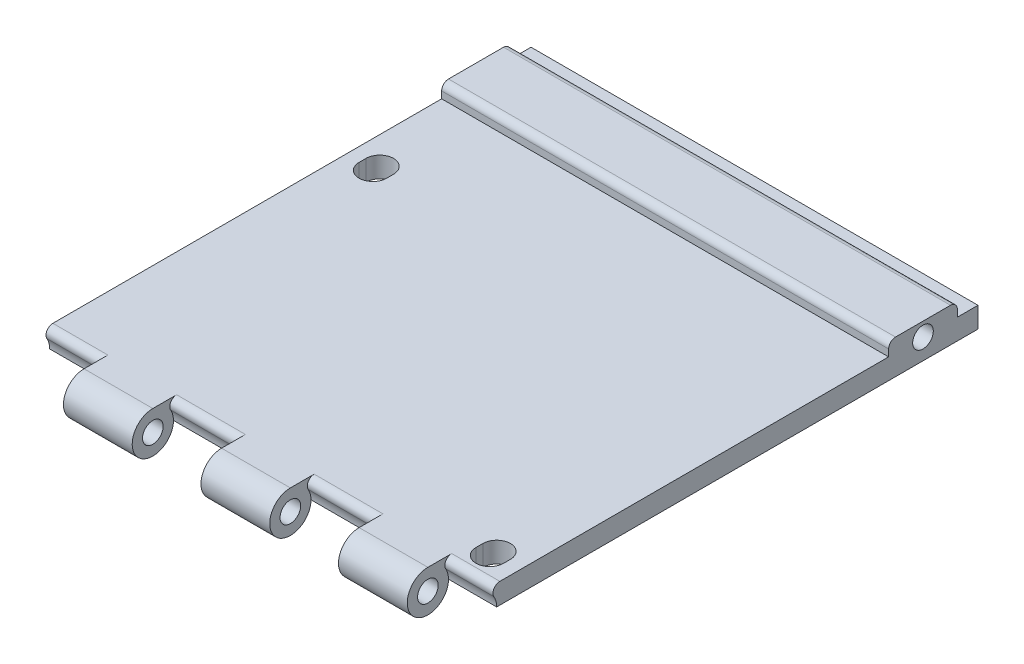
SolidWorks part; units mm, degrees
material "ABS"
ref_plane "Front Plane" through (0, 0, 0) normal (0, 0, 1) x (1, 0, 0)
ref_plane "Top Plane" through (0, 0, 0) normal (0, 1, 0) x (1, 0, 0)
ref_plane "Right Plane" through (0, 0, 0) normal (1, 0, 0) x (0, 0, -1)
sketch "Sketch1" plane through (0, 0, 0) normal (0, 1, 0) x (1, 0, 0)
  line L1 (-32.5, 36.5) -> (32.5, 36.5)
  line L2 (-32.5, 36.5) -> (-32.5, -36.5)
  line L3 (-32.5, -36.5) -> (32.5, -36.5)
  line L4 (32.5, 36.5) -> (32.5, -36.5)
  line L5 (-32.5, 36.5) -> (32.5, -36.5) construction
  line L6 (-32.5, -36.5) -> (32.5, 36.5) construction
  point P0 (0, 0)
  dimension "D1" = 73
  dimension "D2" = 65
extrude "Boss-Extrude1" add sketch "Sketch1" along normal blind 3
sketch "Sketch2" plane through (32.5, 0, 0) normal (1, 0, 0) x (0, 0, -1)
  circle A0 centre (-36.5, 0) radius 3
extrude "Boss-Extrude2" add sketch "Sketch2" against normal through all
sketch "Sketch13" plane through (32.5, 0, 0) normal (1, 0, 0) x (0, 0, -1)
  circle A0 centre (-36.5, 0) radius 1.5
  dimension "D1" = 3
ref_plane "Plane3" through (-24.5, 0, 0) normal (-1, 0, 0) x (0, 0, 1)
ref_plane "Plane4" through (-4.5, 0, 0) normal (-1, 0, 0) x (0, 0, 1)
ref_plane "Plane5" through (15.5, 0, 0) normal (-1, 0, 0) x (0, 0, 1)
sketch "Sketch14" plane through (-24.5, 0, 0) normal (-1, 0, 0) x (0, 0, 1)
  circle A0 centre (36.5, 0) radius 3
extrude "Cut-Extrude1" cut sketch "Sketch14" along normal blind 8
sketch "Sketch15" plane through (-4.5, 0, 0) normal (-1, 0, 0) x (0, 0, 1)
  circle A0 centre (36.5, 0) radius 3
extrude "Cut-Extrude2" cut sketch "Sketch15" along normal blind 10
sketch "Sketch16" plane through (15.5, 0, 0) normal (-1, 0, 0) x (0, 0, 1)
  circle A0 centre (36.5, 0) radius 3
extrude "Cut-Extrude3" cut sketch "Sketch16" along normal blind 10
sketch "Sketch17" plane through (32.5, 0, 0) normal (1, 0, 0) x (0, 0, -1)
  circle A0 centre (-36.5, 0) radius 3
extrude "Cut-Extrude4" cut sketch "Sketch17" against normal blind 7
sketch "Sketch18" plane through (0, 3, 0) normal (0, 1, 0) x (1, 0, 0)
  line L0 (32.5, -38) -> (32.5, -35) construction
  line L1 (-32.5, 36.5) -> (32.5, 36.5) construction
  line L2 (-32.5, 36.5) -> (-32.5, -36.5) construction
  line L3 (-32.5, -36.5) -> (32.5, -36.5) construction
  line L4 (32.5, 36.5) -> (32.5, -36.5) construction
  line L5 (0, -36.5) -> (0, 36.5) construction
  line L6 (-28.5, 10.5) -> (-28.5, 9.5) construction
  line L7 (-32.5, -35) -> (32.5, -35)
  line L8 (-32.5, -35) -> (-32.5, 30)
  line L9 (-32.5, 30) -> (32.5, 30)
  line L10 (32.5, -35) -> (32.5, 30)
  line L11 (-26.5, 10.5) -> (-26.5, 9.5)
  line L12 (-30.5, 10.5) -> (-30.5, 9.5)
  line L13 (28.5, -29.5) -> (28.5, -30.5) construction
  line L14 (30.5, -29.5) -> (30.5, -30.5)
  line L15 (26.5, -29.5) -> (26.5, -30.5)
  arc A0 (-26.5, 10.5) -> (-30.5, 10.5) centre (-28.5, 10.5) ccw
  arc A1 (-30.5, 9.5) -> (-26.5, 9.5) centre (-28.5, 9.5) ccw
  arc A2 (30.5, -29.5) -> (26.5, -29.5) centre (28.5, -29.5) ccw
  arc A3 (26.5, -30.5) -> (30.5, -30.5) centre (28.5, -30.5) ccw
  point P9 (0, -2)
  point P16 (-28.5, 10)
  point P21 (28.5, -30)
  point P33 (28.5, -27.5)
  point P34 (28.5, -32.5)
  dimension "D1" = 65
  dimension "D2" = 65
  dimension "D3" = 1.5
  dimension "D4" = 5
  dimension "D5" = 40
  dimension "D6" = 57
  dimension "D7" = 4
  dimension "D8" = 4
  dimension "D9" = 5
extrude "Cut-Extrude5" cut sketch "Sketch18" against normal blind 7 contours L12 A1 L11 A0 | L15 A3 L14 A2
sketch "Sketch19" plane through (-32.5, 0, 0) normal (-1, 0, 0) x (0, 0, 1)
  line L0 (-28.5, 0) -> (36.5, 0) construction
  line L1 (-28.5, 0) -> (-28.5, 3) construction
  line L2 (-36.5, 3) -> (36.5, 3) construction
  circle A0 centre (-28.5, 3) radius 3
  dimension "D1" = 65
extrude "Boss-Extrude3" add sketch "Sketch19" against normal blind 65
extrude "Cut-Extrude7" cut sketch "Sketch13" against normal through all
sketch "Sketch20" plane through (-32.5, 0, 0) normal (-1, 0, 0) x (0, 0, 1)
  circle A0 centre (-28.5, 3) radius 1.5
  dimension "D1" = 3
extrude "Cut-Extrude8" cut sketch "Sketch20" against normal through all
fillet "Fillet1" radius 1 4 edges at (29, 3, 36.5) (10.5, 3, 36.5) (-9.5, 3, 36.5) (-28.5, 3, 36.5)
sketch "Sketch21" plane through (-32.5, 0, 0) normal (-1, 0, 0) x (0, 0, 1)
  line L0 (-36.5, 0) -> (33.5, 0) construction
  line L1 (-28.5, 3) -> (-28.5, 5) construction
  line L2 (-33.5, 0) -> (-23.5, 0)
  line L3 (-33.5, 0) -> (-33.5, 4)
  line L4 (-32.5, 5) -> (-24.5, 5)
  line L5 (-23.5, 0) -> (-23.5, 4)
  circle A0 centre (-28.5, 3) radius 1.5
  arc A1 (-24.5, 5) -> (-23.5, 4) centre (-24.5, 4) cw
  arc A2 (-33.5, 4) -> (-32.5, 5) centre (-32.5, 4) cw
  point P14 (-33.5, 5)
  dimension "D3" = 1
  dimension "D1" = 5
  dimension "D2" = 10
extrude "Boss-Extrude4" add sketch "Sketch21" against normal through all
sketch "Sketch22" plane through (32.5, 0, 0) normal (1, 0, 0) x (0, 0, -1)
  line L0 (24.5, 5) -> (26.2639, 5) construction
  line L1 (25.382, 5) -> (31.3005, 5)
  line L2 (25.382, 5) -> (25.382, 7.8067)
  line L3 (25.382, 7.8067) -> (31.3005, 7.8067)
  line L4 (31.3005, 5) -> (31.3005, 7.8067)
extrude "Cut-Extrude9" cut sketch "Sketch22" against normal through all
